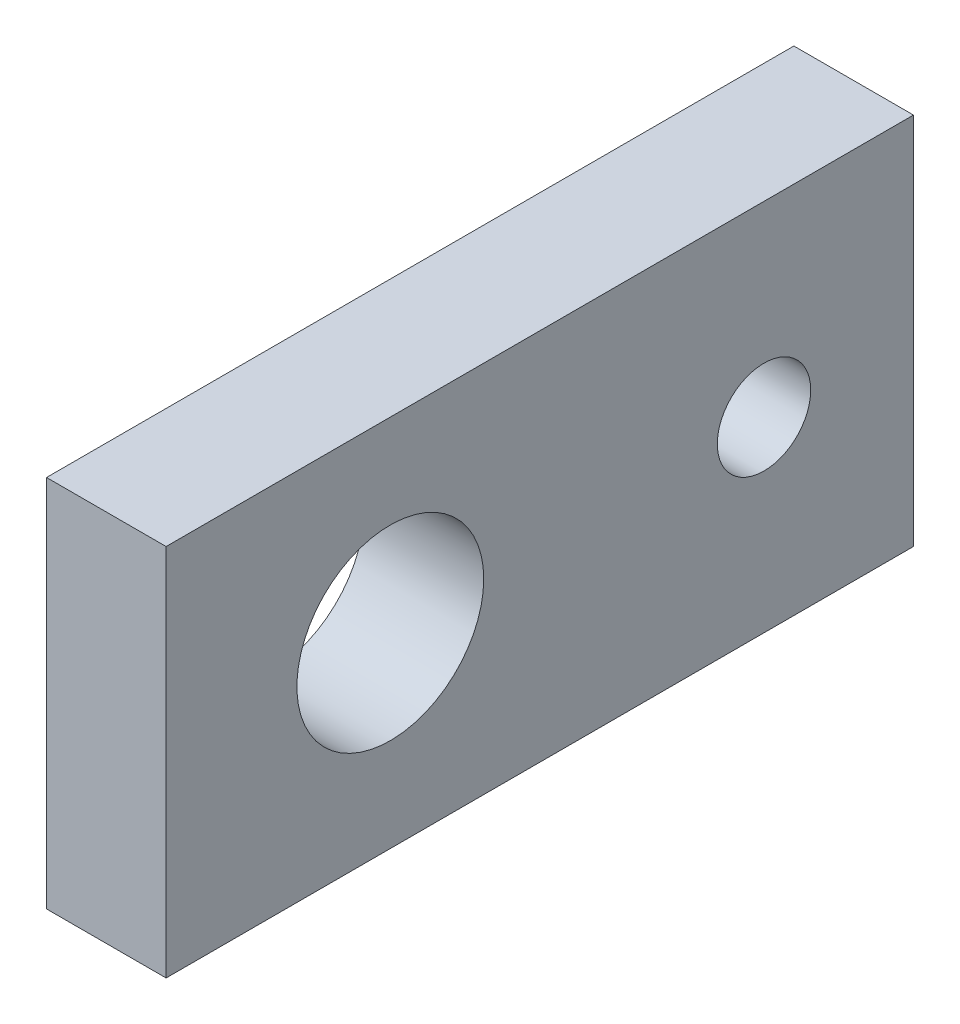
SolidWorks part; units mm, degrees
material "1060 Alloy"
ref_plane "Front Plane" through (0, 0, 0) normal (0, 0, 1) x (1, 0, 0)
ref_plane "Top Plane" through (0, 0, 0) normal (0, 1, 0) x (1, 0, 0)
ref_plane "Right Plane" through (0, 0, 0) normal (1, 0, 0) x (0, 0, -1)
sketch "Sketch1" plane through (0, 0, 0) normal (1, 0, 0) x (0, 0, -1)
  line L1 (0, 0) -> (12.7, 0)
  line L2 (0, 0) -> (0, 6.35)
  line L3 (0, 6.35) -> (12.7, 6.35)
  line L4 (12.7, 0) -> (12.7, 6.35)
  dimension "D1" = 6.35
  dimension "D2" = 12.7
extrude "Boss-Extrude1" add sketch "Sketch1" along normal blind 2.032
hole_wizard "1/16 (0.0625) Diameter Hole1" positions "Sketch3" profile "Sketch2" hole size "1/16" standard "ANSI Inch"
sketch "Sketch3" plane through (2.032, 0, 0) normal (1, 0, 0) x (0, 0, -1)
  line L0 (12.7, 0) -> (12.7, 6.35) construction
  point P2 (10.16, 3.175)
  point P5 (12.7, 3.175)
  dimension "D1" = 0
  dimension "D4" = 2.54
sketch "Sketch2" plane through (2.032, 3.175, -10.16) normal (0, 1, 0) x (0, 0, -1)
  line L0 (0, 0) -> (0, 70.5809)
  line L1 (0, 70.5809) -> (0.7937, 70.104)
  line L2 (0.7937, 70.104) -> (0.7937, 0)
  line L5 (0.7937, 0) -> (0, 0)
  line L10 (0, 70.5809) -> (-0.7938, 70.104) construction
  line L11 (0, -6.35) -> (0, 107.95) construction
  dimension "Hole Dia." = 1.5875
  dimension "Hole Depth" = 70.104
  dimension "Drill Angle" = 118
hole_wizard "1/8 (0.125) Diameter Hole1" positions "Sketch5" profile "Sketch4" hole size "1/8" standard "ANSI Inch"
sketch "Sketch5" plane through (2.032, 0, 0) normal (1, 0, 0) x (0, 0, -1)
  line L0 (12.7, 3.175) -> (0, 3.175) construction
  line L1 (12.7, 0) -> (12.7, 6.35) construction
  line L2 (0, 6.35) -> (0, 0) construction
  circle A1 centre (10.16, 3.175) radius 0.7937 construction
  point P0 (3.81, 3.175)
  dimension "D1" = 6.35
sketch "Sketch4" plane through (2.032, 3.175, -3.81) normal (0, 1, 0) x (0, 0, -1)
  line L0 (0, 0) -> (0, 71.0579)
  line L1 (0, 71.0579) -> (1.5875, 70.104)
  line L2 (1.5875, 70.104) -> (1.5875, 0)
  line L5 (1.5875, 0) -> (0, 0)
  line L10 (0, 71.0579) -> (-1.5875, 70.104) construction
  line L11 (0, -6.35) -> (0, 107.95) construction
  dimension "Hole Dia." = 3.175
  dimension "Hole Depth" = 70.104
  dimension "Drill Angle" = 118
